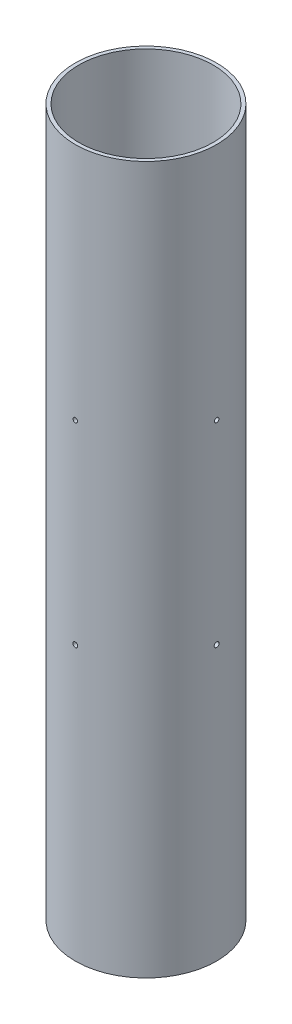
SolidWorks part; units mm, degrees
material "E-Glass Fiber"
ref_plane "Front Plane" through (0, 0, 0) normal (0, 0, 1) x (1, 0, 0)
ref_plane "Top Plane" through (0, 0, 0) normal (0, 1, 0) x (1, 0, 0)
ref_plane "Right Plane" through (0, 0, 0) normal (1, 0, 0) x (0, 0, -1)
sketch "Sketch1" plane through (0, 0, 0) normal (0, 1, 0) x (1, 0, 0)
  circle A0 centre (0, 0) radius 50.8
  dimension "D1" = 101.6
extrude "Coupler Extrusion" add sketch "Sketch1" along normal blind 508 thin thin type one direction reverse wall 2.54
ref_plane "Plane1" through (0, 0, 50.8) normal (0, 0, 1) x (1, 0, 0)
sketch "Sketch2" plane through (0, 0, 50.8) normal (0, 0, 1) x (1, 0, 0)
  line L0 (0, 508) -> (0, 0) construction
  line L1 (48.26, 508) -> (-48.26, 508) construction
  circle A0 centre (0, 336.55) radius 1.6383
  dimension "D1" = 3.2766
  dimension "D2" = 171.45
extrude "Bulkhead Hole" cut sketch "Sketch2" against normal up to next
pattern_circular "CirPattern1" count 4 over 360 about axis through (0, 508, 0) along (0, -1, 0) of "Bulkhead Hole"
sketch "Sketch3" plane through (0, 0, 50.8) normal (0, 0, 1) x (1, 0, 0)
  line L0 (0, 508) -> (0, 0) construction
  line L1 (50.8, 508) -> (-50.8, 508) construction
  line L2 (-48.26, 0) -> (48.26, 0) construction
  line L3 (-50.8, 0) -> (50.8, 0) construction
  line L4 (48.26, 508) -> (-48.26, 508) construction
  circle A0 centre (0, 196.85) radius 1.7526
  dimension "D1" = 3.5052
  dimension "D2" = 196.85
  dimension "D3" = 311.15
extrude "Cut-Extrude1" cut sketch "Sketch3" against normal up to next
pattern_circular "CirPattern2" count 4 over 360 about axis through (0, 508, 0) along (0, -1, 0) of "Cut-Extrude1"
